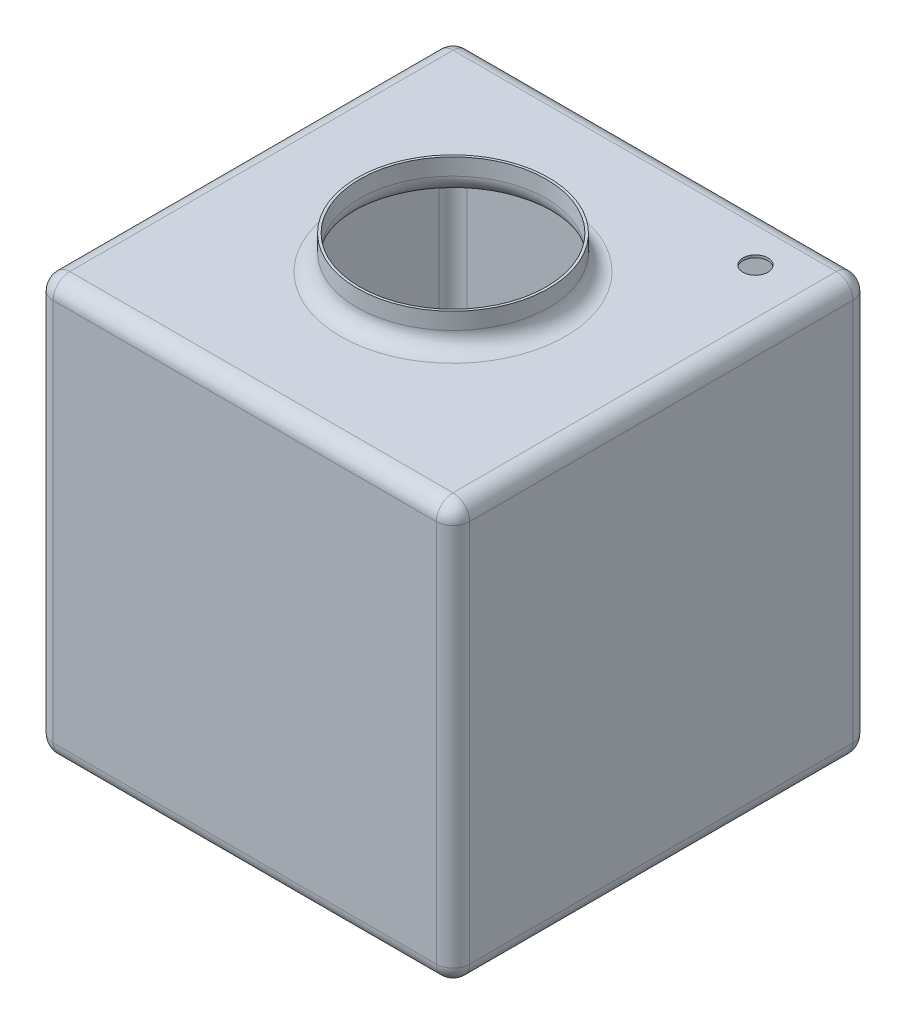
SolidWorks part; units mm, degrees
ref_plane "Alzado" through (0, 0, 0) normal (0, 0, 1) x (1, 0, 0)
ref_plane "Planta" through (0, 0, 0) normal (0, 1, 0) x (1, 0, 0)
ref_plane "Vista lateral" through (0, 0, 0) normal (1, 0, 0) x (0, 0, -1)
sketch "Croquis1" plane through (0, 0, 0) normal (0, 1, 0) x (1, 0, 0)
  line L1 (250, -250) -> (-250, -250)
  line L2 (250, -250) -> (250, 250)
  line L3 (250, 250) -> (-250, 250)
  line L4 (-250, -250) -> (-250, 250)
  line L5 (250, -250) -> (-250, 250) construction
  line L6 (250, 250) -> (-250, -250) construction
  point P0 (0, 0)
  dimension "D1" = 500
  dimension "D2" = 500
extrude "Extruir1" add sketch "Croquis1" along normal blind 500
sketch "Croquis2" plane through (0, 500, 0) normal (0, 1, 0) x (1, 0, 0)
  circle A0 centre (0, 0) radius 115
  dimension "D1" = 230
extrude "Extruir2" add sketch "Croquis2" along normal blind 40
fillet "Redondeo1" radius 20 13 edges at (0, 500, 115) (0, 500, -250) (250, 500, 0) (0, 500, 250) (-250, 500, 0) (0, 0, 250) (250, 0, 0) (0, 0, -250) (-250, 0, 0) (-250, 250, -250) (250, 250, -250) (250, 250, 250) (-250, 250, 250)
shell "Vaciado1" thickness 3
sketch "Croquis3" plane through (0, 500, 0) normal (0, 1, 0) x (1, 0, 0)
  circle A0 centre (174.8283, 188.2209) radius 15
  dimension "D1" = 30
extrude "Extruir3" cut sketch "Croquis3" against normal blind 30
